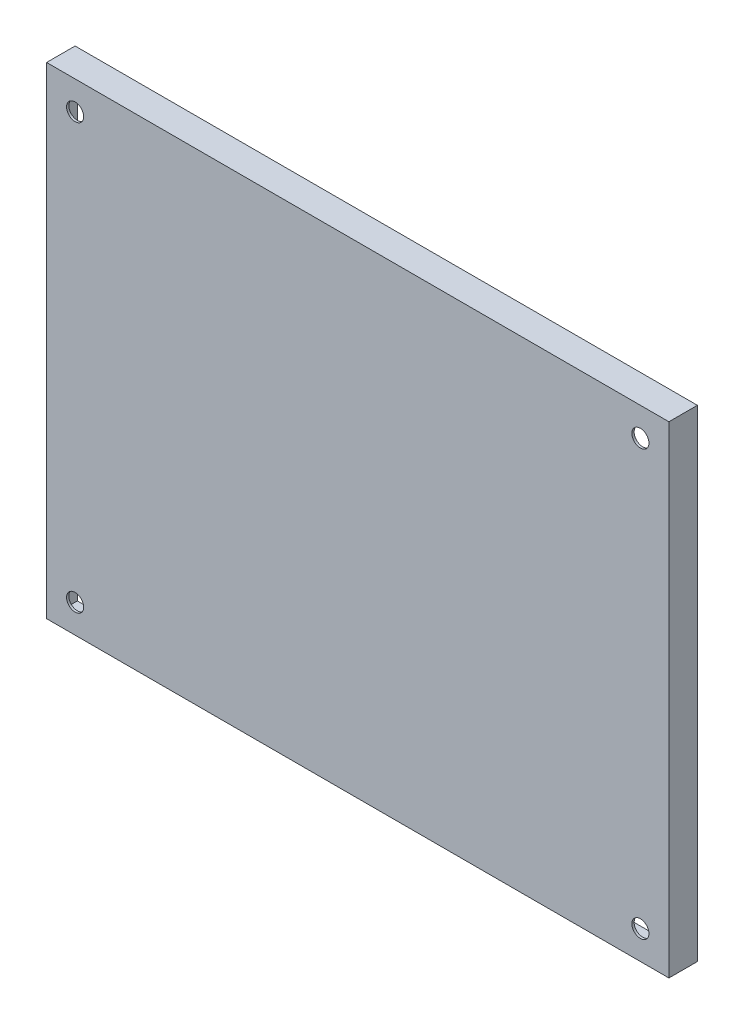
SolidWorks part; units mm, degrees
ref_plane "前视基准面" through (0, 0, 0) normal (0, 0, 1) x (1, 0, 0)
ref_plane "上视基准面" through (0, 0, 0) normal (0, 1, 0) x (1, 0, 0)
ref_plane "右视基准面" through (0, 0, 0) normal (1, 0, 0) x (0, 0, -1)
sketch "草图1" plane through (0, 0, 0) normal (0, 0, 1) x (1, 0, 0)
  line L0 (163.8, -126.8) -> (163.8, 126.8)
  line L1 (163.8, -126.8) -> (-163.8, -126.8)
  line L2 (163.8, 126.8) -> (-163.8, 126.8)
  line L3 (-163.8, -126.8) -> (-163.8, 126.8)
  line L4 (163.8, -126.8) -> (-163.8, 126.8) construction
  line L5 (163.8, 126.8) -> (-163.8, -126.8) construction
  point P1 (0, 0)
  dimension "D1" = 327.6
  dimension "D2" = 253.6
extrude "凸台-拉伸1" add sketch "草图1" along normal blind 15
shell "抽壳1" thickness 1.2
sketch "草图2" plane through (0, 0, 15) normal (0, 0, 1) x (1, 0, 0)
  circle A0 centre (-148.8, 111.8) radius 4.5
  circle A1 centre (148.8, 111.8) radius 4.5
  circle A2 centre (148.8, -111.8) radius 4.5
  circle A3 centre (-148.8, -111.8) radius 4.5
  dimension "D2" = 9
extrude "切除-拉伸1" cut sketch "草图2" against normal blind 15
